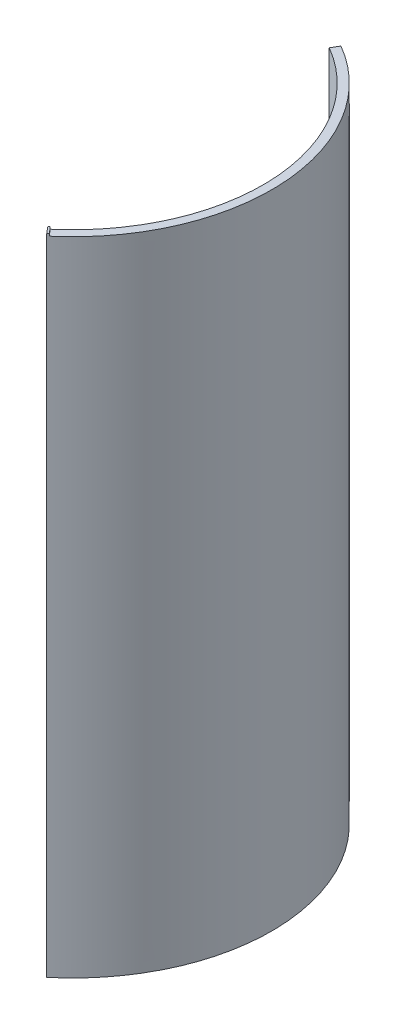
SolidWorks part; units mm, degrees
ref_plane "Front Plane" through (0, 0, 0) normal (0, 0, 1) x (1, 0, 0)
ref_plane "Top Plane" through (0, 0, 0) normal (0, 1, 0) x (1, 0, 0)
ref_plane "Right Plane" through (0, 0, 0) normal (1, 0, 0) x (0, 0, -1)
sketch "Sketch1" plane through (0, 0, 0) normal (0, 1, 0) x (1, 0, 0)
  circle A0 centre (0, 0) radius 27
  dimension "D1" = 54
curve "Helix/Spiral1"
sketch "Sketch2" plane through (0, 0, 0) normal (0, 1, 0) x (1, 0, 0)
  line L0 (0, 0) -> (-30.1249, 0)
  line L1 (0, 0) -> (19.2291, 33.3059)
  line L2 (0, 0) -> (23.3958, -40.5228)
  line L3 (20.1403, 32.884) -> (7.7742, 11.4653) construction
  line L4 (24.2139, -39.9397) -> (8.4815, -12.6904) construction
  line L5 (22.7951, 31.4823) -> (23.7971, 33.2133)
  line L6 (26.6021, -38.0761) -> (27.8832, -39.6119)
  spline S0 degree 3 poles (-2103.5945, 2111.6431) (316.7893, 150.1801) (33.0306, -74.9373) (-23.7329, -14.7754) (-24.7431, -13.4997) (-26.5442, -10.7574) (-27.3351, -9.2909) (-28.6618, -6.2056) (-29.1975, -4.5868) (-29.9849, -1.2422) (-30.2365, 0.4836) (-30.4346, 3.9917) (-30.3812, 5.7739) (-29.9577, 9.3402) (-29.5876, 11.1242) (-28.529, 14.6371) (-27.8404, 16.366) (-26.1532, 19.7113) (-25.1546, 21.3277) (-22.8664, 24.3921) (-21.5767, 25.8399) (-18.7354, 28.5146) (-17.1837, 29.7413) (-13.857, 31.926) (-12.082, 32.884) (-8.3558, 34.4906) (-6.4048, 35.1391) (-2.3811, 36.0946) (-0.3086, 36.4014) (3.8974, 36.6511) (6.0308, 36.5938) (10.2939, 36.1036) (12.4236, 35.6706) (16.6125, 34.4288) (18.6717, 33.62) (22.6527, 31.6384) (24.5746, 30.4656) (28.2163, 27.7801) (29.9361, 26.2672) (33.1132, 22.9369) (34.5704, 21.1194) (37.1683, 17.2258) (38.3089, 15.1498) (40.2275, 10.7951) (41.0054, 8.5164) (42.1627, 3.8204) (42.542, 1.4031) (42.8775, -3.5) (42.8337, -5.9856) (42.3107, -10.9506) (41.8316, -13.4299) (40.4394, -18.3055) (39.5262, -20.7017) (37.2807, -25.3346) (35.9483, -27.5713) (32.8926, -31.8113) (31.1694, -33.8147) (27.3732, -37.5197) (25.3004, -39.2211) (20.8587, -42.2611) (18.4898, -43.5996) (13.52, -45.8618) (10.9192, -46.7856) (-103.0489, -76.3947) (-351.1457, 286.8338) (2125.4363, 2012.5924) knots -1.551294 -1.551294 -1.551294 -1.551294 0.03125 0.03125 0.0625 0.0625 0.09375 0.09375 0.125 0.125 0.15625 0.15625 0.1875 0.1875 0.21875 0.21875 0.25 0.25 0.28125 0.28125 0.3125 0.3125 0.34375 0.34375 0.375 0.375 0.40625 0.40625 0.4375 0.4375 0.46875 0.46875 0.5 0.5 0.53125 0.53125 0.5625 0.5625 0.59375 0.59375 0.625 0.625 0.65625 0.65625 0.6875 0.6875 0.71875 0.71875 0.75 0.75 0.78125 0.78125 0.8125 0.8125 0.84375 0.84375 0.875 0.875 0.90625 0.90625 0.9375 0.9375 0.96875 0.96875 2.266286 2.266286 2.266286 2.266286 only from (-19.0919, -19.0919) to (0, -48.875) construction
  spline S1 degree 3 poles (-19.0919, -19.0919) (-20.3464, -18.1596) (-21.5345, -17.1054) (-23.7329, -14.7754) (-24.7431, -13.4997) (-26.5442, -10.7574) (-27.3351, -9.2909) (-28.6618, -6.2056) (-29.1975, -4.5868) (-29.9849, -1.2422) (-30.2365, 0.4836) (-30.4346, 3.9917) (-30.3812, 5.7739) (-29.9577, 9.3402) (-29.5876, 11.1242) (-28.529, 14.6371) (-27.8404, 16.366) (-26.1532, 19.7113) (-25.1546, 21.3277) (-22.8664, 24.3921) (-21.5767, 25.8399) (-18.7354, 28.5146) (-17.1837, 29.7413) (-13.857, 31.926) (-12.082, 32.884) (-8.3558, 34.4906) (-6.4048, 35.1391) (-2.3811, 36.0946) (-0.3086, 36.4014) (3.8974, 36.6511) (6.0308, 36.5938) (10.2939, 36.1036) (12.4236, 35.6706) (16.6125, 34.4288) (18.6717, 33.62) (22.6527, 31.6384) (24.5746, 30.4656) (28.2163, 27.7801) (29.9361, 26.2672) (33.1132, 22.9369) (34.5704, 21.1194) (37.1683, 17.2258) (38.3089, 15.1498) (40.2275, 10.7951) (41.0054, 8.5164) (42.1627, 3.8204) (42.542, 1.4031) (42.8775, -3.5) (42.8337, -5.9856) (42.3107, -10.9506) (41.8316, -13.4299) (40.4394, -18.3055) (39.5262, -20.7017) (37.2807, -25.3346) (35.9483, -27.5713) (32.8926, -31.8113) (31.1694, -33.8147) (27.3732, -37.5197) (25.3004, -39.2211) (20.8587, -42.2611) (18.4898, -43.5996) (13.52, -45.8618) (10.9192, -46.7856) (5.5586, -48.1783) (2.799, -48.6471) (0, -48.875) knots 0 0 0 0 0.03125 0.03125 0.0625 0.0625 0.09375 0.09375 0.125 0.125 0.15625 0.15625 0.1875 0.1875 0.21875 0.21875 0.25 0.25 0.28125 0.28125 0.3125 0.3125 0.34375 0.34375 0.375 0.375 0.40625 0.40625 0.4375 0.4375 0.46875 0.46875 0.5 0.5 0.53125 0.53125 0.5625 0.5625 0.59375 0.59375 0.625 0.625 0.65625 0.65625 0.6875 0.6875 0.71875 0.71875 0.75 0.75 0.78125 0.78125 0.8125 0.8125 0.84375 0.84375 0.875 0.875 0.90625 0.90625 0.9375 0.9375 0.96875 0.96875 1 1 1 1
  spline S2 degree 1 poles (-20.2848, -20.6972) (0.1623, -50.8684) knots 0 0 1 1 construction
  spline S3 degree 3 poles (-20.2848, -20.6972) (-21.6469, -19.6849) (-24.1785, -17.4352) (-28.5209, -11.9579) (-32.1495, -3.6002) (-32.8349, 7.7935) (-29.4442, 19.1835) (-22.0836, 29.1084) (-11.3827, 36.1844) (1.5498, 39.2971) (12.6426, 38.0546) (21.033, 34.8691) (25.8636, 32.0782) (31.7987, 27.52) (38.5762, 19.989) (44.3682, 6.9371) (45.4784, -8.6935) (41.1215, -24.1009) (34.3866, -33.5725) (28.964, -38.7297) (26.7177, -40.604) (22.6326, -43.5587) (16.9541, -46.7674) (10.1773, -49.1736) (4.5155, -50.3869) (1.6139, -50.7502) (0.1623, -50.8684) knots 0 0 0 0 0.03125 0.0625 0.125 0.1875 0.25 0.3125 0.375 0.4375 0.5 0.526936 0.558186 0.573811 0.625 0.6875 0.75 0.8125 0.873453 0.881266 0.896891 0.90625 0.9375 0.96875 0.984375 1 1 1 1
  dimension "D2" = 120
  dimension "D3" = 120
  dimension "D4" = 1
  dimension "D5" = 1
  dimension "D6" = 3
  dimension "D7" = 3
  dimension "D1" = 2
extrude "Boss-Extrude1" add sketch "Sketch2" along normal blind 150 contours S3 L5 S1 L6
sketch "Sketch3" plane through (0, 150, 0) normal (0, 1, 0) x (1, 0, 0)
  line L2 (26.9108, -37.8163) -> (28.2053, -39.3408)
  line L4 (23.7971, 33.2133) -> (22.7951, 31.4823)
  line L5 (26.6021, -38.0761) -> (27.8832, -39.6119)
  line L6 (23.7971, 33.2133) -> (22.7951, 31.4823)
  line L7 (26.6021, -38.0761) -> (27.8832, -39.6119)
  spline S4 degree 3 poles (1352.0826, 3678.2269) (-532.745, 139.1591) (-62.4103, -125.6315) (34.3866, -33.5725) (41.1215, -24.1009) (45.4784, -8.6935) (44.3682, 6.9371) (38.5762, 19.989) (31.7987, 27.52) (-65.9258, 102.5731) (-417.2225, -276.923) (3128.2208, -2428.754) knots -0.88728 -0.88728 -0.88728 -0.88728 0.550374 0.558186 0.61914 0.68164 0.74414 0.80664 0.857828 0.873453 2.421303 2.421303 2.421303 2.421303 only from (27.8832, -39.6119) to (23.7971, 33.2133)
  spline S5 degree 3 poles (3040.6686, -2538.78) (-408.7244, -262.3168) (-64.7221, 96.3178) (28.2163, 27.7801) (29.9361, 26.2672) (33.1132, 22.9369) (34.5704, 21.1194) (37.1683, 17.2258) (38.3089, 15.1498) (40.2275, 10.7951) (41.0054, 8.5164) (42.1627, 3.8204) (42.542, 1.4031) (42.8775, -3.5) (42.8337, -5.9856) (42.3107, -10.9506) (41.8316, -13.4299) (40.4394, -18.3055) (39.5262, -20.7017) (37.2807, -25.3346) (35.9483, -27.5713) (32.8926, -31.8113) (31.1694, -33.8147) (-58.5959, -121.424) (-520.9551, 116.3719) (1288.2462, 3705.4606) knots -1.001288 -1.001288 -1.001288 -1.001288 0.5625 0.5625 0.59375 0.59375 0.625 0.625 0.65625 0.65625 0.6875 0.6875 0.71875 0.71875 0.75 0.75 0.78125 0.78125 0.8125 0.8125 0.84375 0.84375 0.875 0.875 2.321665 2.321665 2.321665 2.321665 only from (22.7951, 31.4823) to (26.6021, -38.0761)
  spline S6 degree 3 poles (27.8832, -39.6119) (28.4179, -39.1659) (29.466, -38.2523) (34.3866, -33.5725) (41.1215, -24.1009) (45.4784, -8.6935) (44.3682, 6.9371) (38.5762, 19.989) (31.7987, 27.52) (26.8093, 31.3519) (24.8154, 32.6239) (23.7971, 33.2133) knots 0.542561 0.542561 0.542561 0.542561 0.550374 0.558186 0.61914 0.68164 0.74414 0.80664 0.857828 0.873453 0.889078 0.889078 0.889078 0.889078
  spline S7 degree 3 poles (22.7951, 31.4823) (24.0308, 30.7671) (25.2336, 29.9796) (28.2163, 27.7801) (29.9361, 26.2672) (33.1132, 22.9369) (34.5704, 21.1194) (37.1683, 17.2258) (38.3089, 15.1498) (40.2275, 10.7951) (41.0054, 8.5164) (42.1627, 3.8204) (42.542, 1.4031) (42.8775, -3.5) (42.8337, -5.9856) (42.3107, -10.9506) (41.8316, -13.4299) (40.4394, -18.3055) (39.5262, -20.7017) (37.2807, -25.3346) (35.9483, -27.5713) (32.8926, -31.8113) (31.1694, -33.8147) (28.4162, -36.5017) (27.5257, -37.3057) (26.6021, -38.0761) knots 0.542561 0.542561 0.542561 0.542561 0.5625 0.5625 0.59375 0.59375 0.625 0.625 0.65625 0.65625 0.6875 0.6875 0.71875 0.71875 0.75 0.75 0.78125 0.78125 0.8125 0.8125 0.84375 0.84375 0.875 0.875 0.889078 0.889078 0.889078 0.889078
  spline M6 degree 3 poles (0.1623, -50.8684) (1.6139, -50.7502) (4.5155, -50.3869) (10.1773, -49.1736) (16.9541, -46.7674) (22.6326, -43.5587) (26.7177, -40.604) (28.964, -38.7297) (34.3866, -33.5725) (41.1215, -24.1009) (45.4784, -8.6935) (44.3682, 6.9371) (38.5762, 19.989) (31.7987, 27.52) (25.8636, 32.0782) (21.033, 34.8691) (12.6426, 38.0546) (1.5498, 39.2971) (-11.3827, 36.1844) (-22.0836, 29.1084) (-29.4442, 19.1835) (-32.8349, 7.7935) (-32.1495, -3.6002) (-28.5209, -11.9579) (-24.1785, -17.4352) (-21.6469, -19.6849) (-20.2848, -20.6972) knots 0 0 0 0 0.015625 0.03125 0.0625 0.09375 0.103109 0.118734 0.126547 0.1875 0.25 0.3125 0.375 0.426189 0.441814 0.473064 0.5 0.5625 0.625 0.6875 0.75 0.8125 0.875 0.9375 0.96875 1 1 1 1 only from (27.8832, -39.6119) to (23.7971, 33.2133)
  spline M8 degree 3 poles (-19.0919, -19.0919) (-20.3464, -18.1596) (-21.5345, -17.1054) (-23.7329, -14.7754) (-24.7431, -13.4997) (-26.5442, -10.7574) (-27.3351, -9.2909) (-28.6618, -6.2056) (-29.1975, -4.5868) (-29.9849, -1.2422) (-30.2365, 0.4836) (-30.4346, 3.9917) (-30.3812, 5.7739) (-29.9577, 9.3402) (-29.5876, 11.1242) (-28.529, 14.6371) (-27.8404, 16.366) (-26.1532, 19.7113) (-25.1546, 21.3277) (-22.8664, 24.3921) (-21.5767, 25.8399) (-18.7354, 28.5146) (-17.1837, 29.7413) (-13.857, 31.926) (-12.082, 32.884) (-8.3558, 34.4906) (-6.4048, 35.1391) (-2.3811, 36.0946) (-0.3086, 36.4014) (3.8974, 36.6511) (6.0308, 36.5938) (10.2939, 36.1036) (12.4236, 35.6706) (16.6125, 34.4288) (18.6717, 33.62) (22.6527, 31.6384) (24.5746, 30.4656) (28.2163, 27.7801) (29.9361, 26.2672) (33.1132, 22.9369) (34.5704, 21.1194) (37.1683, 17.2258) (38.3089, 15.1498) (40.2275, 10.7951) (41.0054, 8.5164) (42.1627, 3.8204) (42.542, 1.4031) (42.8775, -3.5) (42.8337, -5.9856) (42.3107, -10.9506) (41.8316, -13.4299) (40.4394, -18.3055) (39.5262, -20.7017) (37.2807, -25.3346) (35.9483, -27.5713) (32.8926, -31.8113) (31.1694, -33.8147) (27.3732, -37.5197) (25.3004, -39.2211) (20.8587, -42.2611) (18.4898, -43.5996) (13.52, -45.8618) (10.9192, -46.7856) (5.5586, -48.1783) (2.799, -48.6471) (0, -48.875) knots 0 0 0 0 0.03125 0.03125 0.0625 0.0625 0.09375 0.09375 0.125 0.125 0.15625 0.15625 0.1875 0.1875 0.21875 0.21875 0.25 0.25 0.28125 0.28125 0.3125 0.3125 0.34375 0.34375 0.375 0.375 0.40625 0.40625 0.4375 0.4375 0.46875 0.46875 0.5 0.5 0.53125 0.53125 0.5625 0.5625 0.59375 0.59375 0.625 0.625 0.65625 0.65625 0.6875 0.6875 0.71875 0.71875 0.75 0.75 0.78125 0.78125 0.8125 0.8125 0.84375 0.84375 0.875 0.875 0.90625 0.90625 0.9375 0.9375 0.96875 0.96875 1 1 1 1 only from (22.7951, 31.4823) to (26.6021, -38.0761)
  line M9 (26.6021, -38.0761) -> (27.8832, -39.6119)
  dimension "D2" = 0.5
  dimension "D1" = 0
extrude "Boss-Extrude2" add sketch "Sketch3" along normal blind 0.5 contours L2 M8 M9 M6
